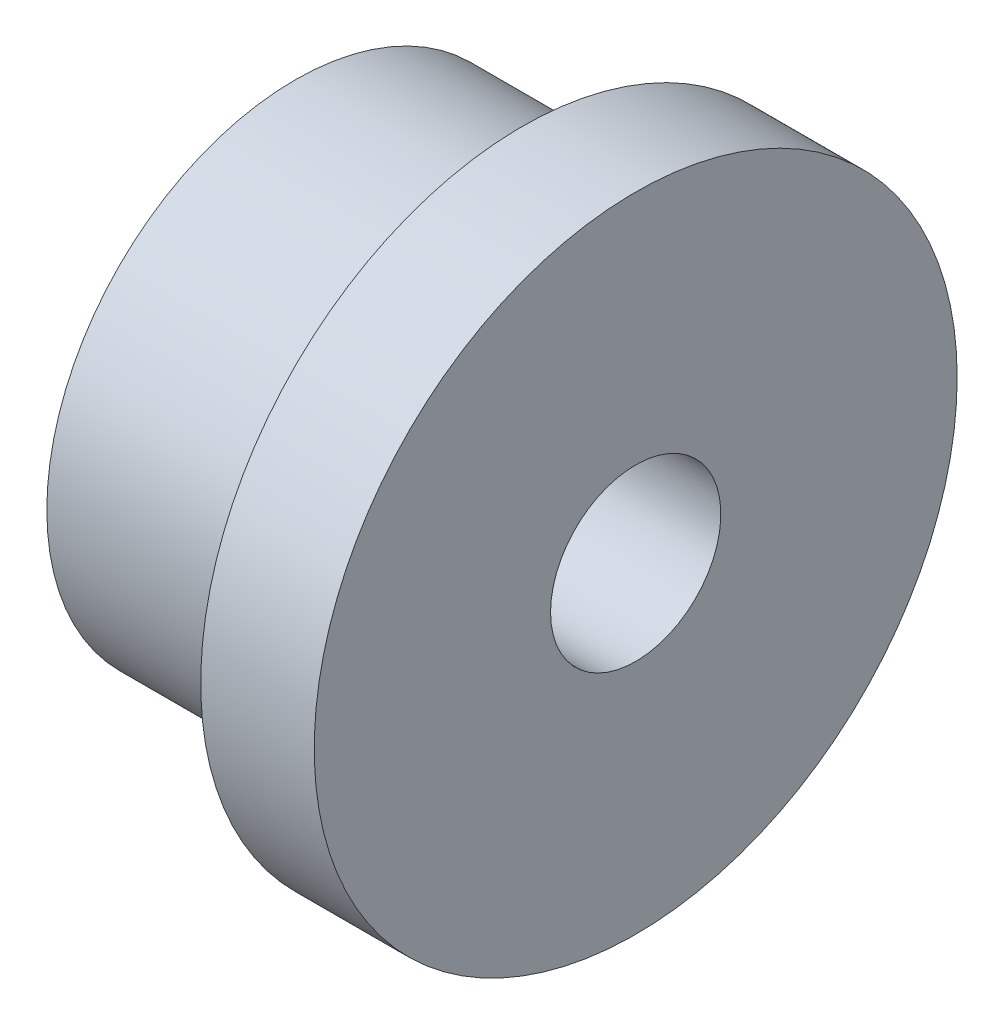
SolidWorks part; units mm, degrees
material "Nylon 101"
ref_plane "Front Plane" through (0, 0, 0) normal (0, 0, 1) x (1, 0, 0)
ref_plane "Top Plane" through (0, 0, 0) normal (0, 1, 0) x (1, 0, 0)
ref_plane "Right Plane" through (0, 0, 0) normal (1, 0, 0) x (0, 0, -1)
sketch "Sketch1" plane through (0, 0, 0) normal (1, 0, 0) x (0, 0, -1)
  circle A0 centre (0, 0) radius 8.9916
  dimension "D1" = 17.9832
extrude "Boss-Extrude1" add sketch "Sketch1" along normal blind 3.175
sketch "Sketch2" plane through (0, 0, 0) normal (-1, 0, 0) x (0, 0, 1)
  circle A0 centre (0, 0) radius 6.9453
  dimension "D1" = 13.8906
extrude "Boss-Extrude2" add sketch "Sketch2" along normal blind 6.35
hole_wizard "#21 (0.159) Diameter Hole1" positions "Sketch4" profile "Sketch3" hole size "#21" standard "ANSI Inch" end condition through all
sketch "Sketch4" plane through (-6.35, 0, 0) normal (-1, 0, 0) x (0, 0, 1)
  point P0 (0, 0)
sketch "Sketch3" plane through (-6.35, 0, 0) normal (0, 1, 0) x (0, 0, 1)
  line L0 (0, 0) -> (0, 9.525)
  line L1 (0, 9.525) -> (2.3812, 9.525)
  line L2 (2.3812, 9.525) -> (2.3812, 0)
  line L5 (2.3812, 0) -> (0, 0)
  line L11 (0, -6.35) -> (0, 107.95) construction
  dimension "Thru Hole Dia." = 4.7625
  dimension "Thru Hole Depth" = 9.525
